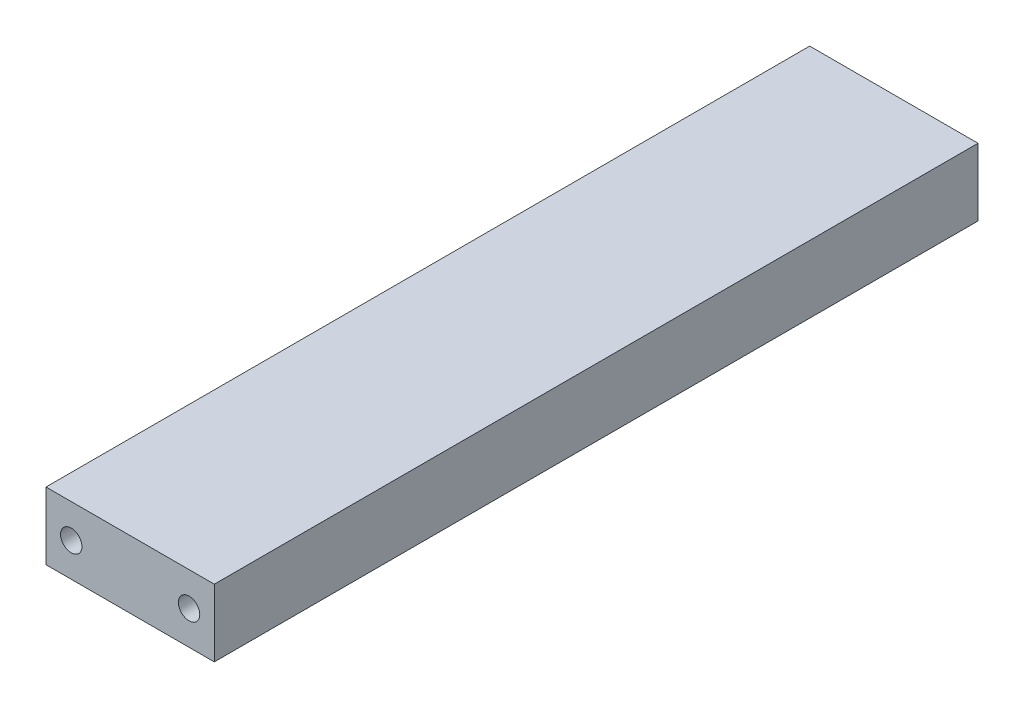
SolidWorks part; units mm, degrees
ref_plane "Front Plane" through (0, 0, 0) normal (0, 0, 1) x (1, 0, 0)
ref_plane "Top Plane" through (0, 0, 0) normal (0, 1, 0) x (1, 0, 0)
ref_plane "Right Plane" through (0, 0, 0) normal (1, 0, 0) x (0, 0, -1)
sketch "Sketch1" plane through (0, 0, 0) normal (0, 0, 1) x (1, 0, 0)
  line L1 (-15.875, 6.35) -> (15.875, 6.35)
  line L2 (-15.875, 6.35) -> (-15.875, -6.35)
  line L3 (-15.875, -6.35) -> (15.875, -6.35)
  line L4 (15.875, 6.35) -> (15.875, -6.35)
  line L5 (-15.875, 6.35) -> (15.875, -6.35) construction
  line L6 (-15.875, -6.35) -> (15.875, 6.35) construction
  point P0 (0, 0)
  dimension "D1" = 31.75
  dimension "D2" = 12.7
extrude "Boss-Extrude1" add sketch "Sketch1" along normal offset from surface (144.0658 mm away) 5
hole_wizard "#10-32 Tapped Hole1" positions "Sketch3" profile "Sketch2" tap size "#10-32" standard "ANSI Inch"
sketch "Sketch3" plane through (0, -9.125, 144.0658) normal (0, 0, -1) x (1, 0, 0)
  line L0 (-11.1125, -9.125) -> (11.1125, -9.125) construction
  line L2 (0, -9.125) -> (0, -15.475) construction
  line L3 (15.875, -15.475) -> (-15.875, -15.475) construction
  line L6 (-15.875, -2.775) -> (15.875, -2.775) construction
  line L7 (15.875, -15.475) -> (-15.875, -15.475) construction
  point P0 (-11.1125, -9.125)
  point P2 (11.1125, -9.125)
  dimension "D1" = 22.225
sketch "Sketch2" plane through (-11.1125, 0, 144.0658) normal (1, 0, 0) x (0, -1, 0)
  line L0 (0, 0) -> (0, 12.03)
  line L1 (0, 12.03) -> (2.0193, 12.03)
  line L2 (2.0193, 12.03) -> (2.0193, 0)
  line L5 (2.0193, 0) -> (0, 0)
  line L10 (0, 12.03) -> (-2.0193, 12.03) construction
  line L11 (0, -6.35) -> (0, 107.95) construction
  dimension "Tap Drill Dia." = 4.0386
  dimension "Tap Drill Depth" = 12.03
  dimension "Drill Angle" = 180
cosmetic thread "Hole Thread3" parameters "D1"=9.65, "D2"=4.826
cosmetic thread "Hole Thread4" parameters "D1"=9.65, "D2"=4.826
ref_plane "Plane1" through (0, 0, 72.0329) normal (0, 0, 1) x (1, 0, 0)
mirror "Mirror1" about plane through (0, 0, 72.0329) normal (0, 0, 1) of "#10-32 Tapped Hole1"
